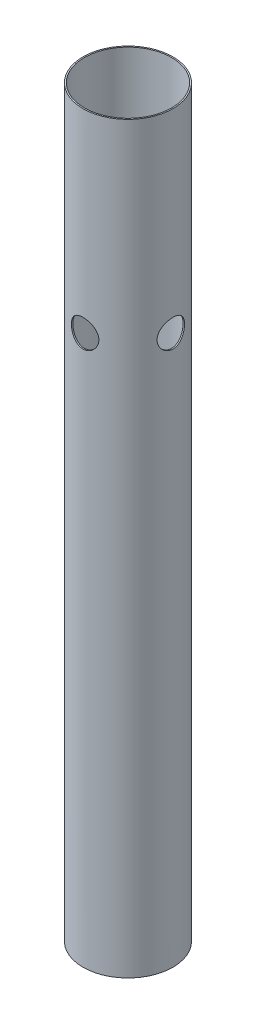
SolidWorks part; units mm, degrees
ref_plane "Front Plane" through (0, 0, 0) normal (0, 0, 1) x (1, 0, 0)
ref_plane "Top Plane" through (0, 0, 0) normal (0, 1, 0) x (1, 0, 0)
ref_plane "Right Plane" through (0, 0, 0) normal (1, 0, 0) x (0, 0, -1)
sketch "Sketch2" plane through (0, 0, 0) normal (0, 1, 0) x (1, 0, 0)
  circle A0 centre (0, 0) radius 38.15
  circle A1 centre (0, 0) radius 39.3
  dimension "D1" = 78.6
  dimension "D2" = 76.3
extrude "Boss-Extrude1" add sketch "Sketch2" along normal blind 650
sketch "Sketch3" plane through (0, 0, 0) normal (0, 0, 1) x (1, 0, 0)
  line L0 (38.15, 650) -> (-38.15, 650) construction
  circle A1 centre (0, 480) radius 12
  dimension "D2" = 170
extrude "Cut-Extrude1" cut sketch "Sketch3" against normal through all
ref_axis "Axis1" through (0, 650, 0) along (0, -1, 0)
pattern_circular "CirPattern1" count 4 over 360 about axis through (0, 650, 0) along (0, -1, 0) of "Cut-Extrude1"
